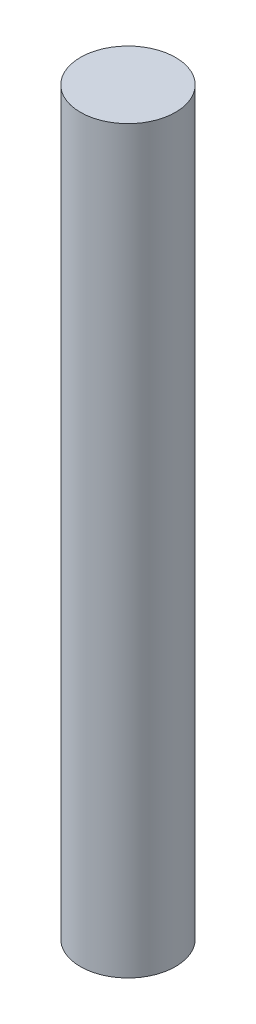
SolidWorks part; units mm, degrees
ref_plane "Front Plane" through (0, 0, 0) normal (0, 0, 1) x (1, 0, 0)
ref_plane "Top Plane" through (0, 0, 0) normal (0, 1, 0) x (1, 0, 0)
ref_plane "Right Plane" through (0, 0, 0) normal (1, 0, 0) x (0, 0, -1)
sketch "Sketch1" plane through (0, 0, 0) normal (0, 1, 0) x (1, 0, 0)
  circle A0 centre (0, 0) radius 2.25
  dimension "D1" = 4.5
extrude "Boss-Extrude1" add sketch "Sketch1" along normal blind 35
